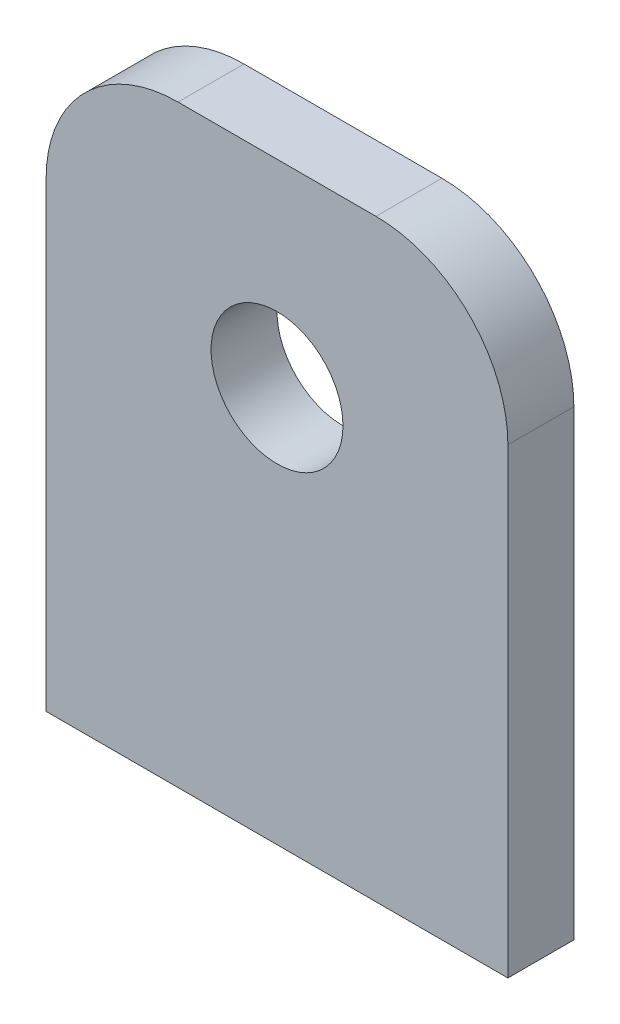
SolidWorks part; units mm, degrees
ref_plane "Front Plane" through (0, 0, 0) normal (0, 0, 1) x (1, 0, 0)
ref_plane "Top Plane" through (0, 0, 0) normal (0, 1, 0) x (1, 0, 0)
ref_plane "Right Plane" through (0, 0, 0) normal (1, 0, 0) x (0, 0, -1)
sketch "Sketch1" plane through (0, 0, 0) normal (0, 0, 1) x (1, 0, 0)
  line L1 (-11.1125, -14.2875) -> (11.1125, -14.2875)
  line L2 (-11.1125, -14.2875) -> (-11.1125, 14.2875)
  line L3 (-11.1125, 14.2875) -> (11.1125, 14.2875)
  line L4 (11.1125, -14.2875) -> (11.1125, 14.2875)
  line L5 (-11.1125, -14.2875) -> (11.1125, 14.2875) construction
  line L6 (-11.1125, 14.2875) -> (11.1125, -14.2875) construction
  point P0 (0, 0)
  dimension "D1" = 22.225
  dimension "D2" = 28.575
extrude "Boss-Extrude1" add sketch "Sketch1" along normal blind 3.175
fillet "Fillet1" radius 6.35 2 edges at (-11.1125, 14.2875, 1.5875) (11.1125, 14.2875, 1.5875)
sketch "Sketch2" plane through (0, 0, 3.175) normal (0, 0, 1) x (1, 0, 0)
  line L0 (0, 0) -> (0, 4.7625) construction
  line L1 (4.7625, 14.2875) -> (-4.7625, 14.2875) construction
  circle A0 centre (0, 4.7625) radius 3.175
  dimension "D1" = 6.35
  dimension "D2" = 9.525
extrude "Cut-Extrude1" cut sketch "Sketch2" against normal through all
